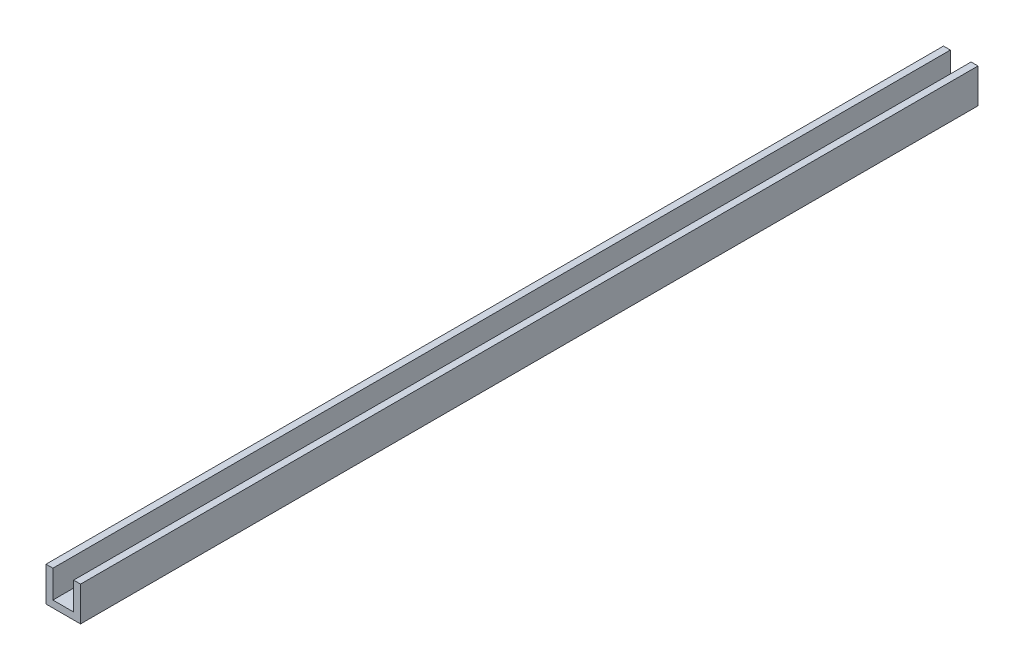
SolidWorks part; units mm, degrees
ref_plane "Plan de face" through (0, 0, 0) normal (0, 0, 1) x (1, 0, 0)
ref_plane "Plan de dessus" through (0, 0, 0) normal (0, 1, 0) x (1, 0, 0)
ref_plane "Plan de droite" through (0, 0, 0) normal (1, 0, 0) x (0, 0, -1)
sketch "Esquisse1" plane through (0, 0, 0) normal (0, 0, 1) x (1, 0, 0)
  line L0 (0, 0) -> (0, -10)
  line L1 (0, -10) -> (10, -10)
  line L2 (10, -10) -> (10, 0)
  line L3 (10, 0) -> (8, 0)
  line L4 (8, 0) -> (8, -8)
  line L5 (8, -8) -> (2, -8)
  line L6 (2, -8) -> (2, 0)
  line L7 (2, 0) -> (0, 0)
  dimension "D1" = 10
  dimension "D2" = 10
  dimension "D3" = 2
  dimension "D4" = 2
  dimension "D5" = 2
extrude "Boss.-Extru.1" add sketch "Esquisse1" along normal blind 260
sketch "Esquisse2" plane through (0, -10, 0) normal (0, -1, 0) x (1, 0, 0)
  line L0 (0, 260) -> (10, 260) construction
  line L1 (10, 260) -> (10, 0) construction
  circle A0 centre (5, 214.21) radius 1.25
  dimension "D1" = 2.5
  dimension "D2" = 45.79
  dimension "D3" = 5
extrude "Enlèv. mat.-Extru.1" cut sketch "Esquisse2" against normal blind 10
sketch "Esquisse3" plane through (0, -10, 0) normal (0, -1, 0) x (-1, 0, 0)
  line L0 (0, -260) -> (0, 0) construction
  line L1 (0, 0) -> (-10, 0) construction
  circle A0 centre (-5, -5) radius 1.25
  circle A1 centre (-5, -55) radius 1.25
  dimension "D1" = 2.5
  dimension "D4" = 2.5
  dimension "D2" = 5
  dimension "D3" = 5
  dimension "D5" = 50
extrude "Enlèv. mat.-Extru.2" cut sketch "Esquisse3" against normal blind 10
